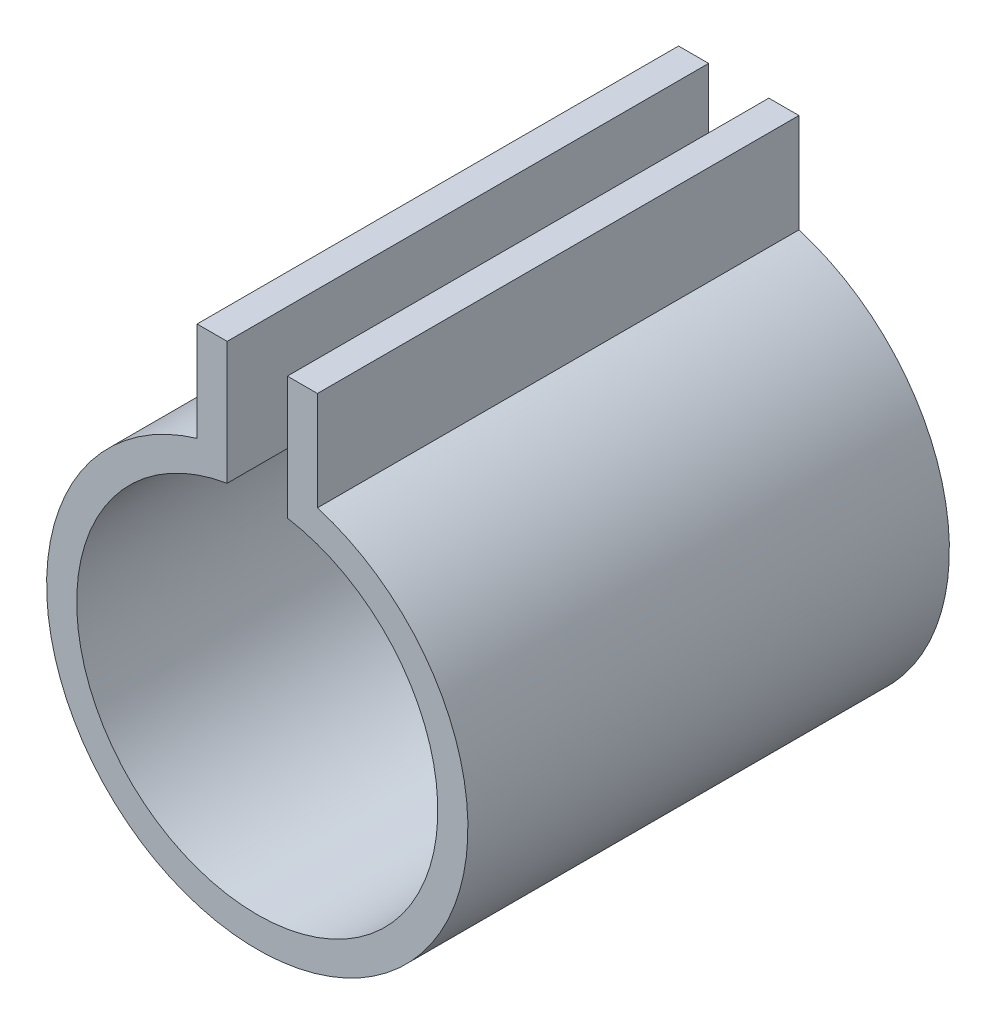
SolidWorks part; units mm, degrees
ref_plane "Front" through (0, 0, 0) normal (0, 0, 1) x (1, 0, 0)
ref_plane "Top" through (0, 0, 0) normal (0, 1, 0) x (1, 0, 0)
ref_plane "Right" through (0, 0, 0) normal (1, 0, 0) x (0, 0, -1)
sketch "Sketch2" plane through (0, 0, 0) normal (0, 0, 1) x (1, 0, 0)
  line L0 (0, 0) -> (0, 31.75) construction
  line L1 (3.175, 22.86) -> (3.175, 31.75)
  line L2 (3.175, 31.75) -> (6.35, 31.75)
  line L3 (6.35, 31.75) -> (6.35, 21.2985)
  line L4 (3.175, 31.75) -> (0, 31.75) construction
  line L5 (3.175, 22.86) -> (3.175, 18.7836)
  line L6 (-6.35, 31.75) -> (-6.35, 21.2985)
  line L7 (-3.175, 31.75) -> (-6.35, 31.75)
  line L8 (-3.175, 22.86) -> (-3.175, 18.7836)
  line L9 (-3.175, 22.86) -> (-3.175, 31.75)
  arc A0 (-3.175, 18.7836) -> (3.175, 18.7836) centre (0, 0) ccw
  arc A1 (-6.35, 21.2985) -> (6.35, 21.2985) centre (0, 0) ccw
  dimension "D1" = 38.1
  dimension "D2" = 44.45
  dimension "D3" = 3.175
  dimension "D4" = 3.175
  dimension "D5" = 8.89
  dimension "D6" = 31.75
extrude "Boss-Extrude1" add sketch "Sketch2" along normal blind 50.8
